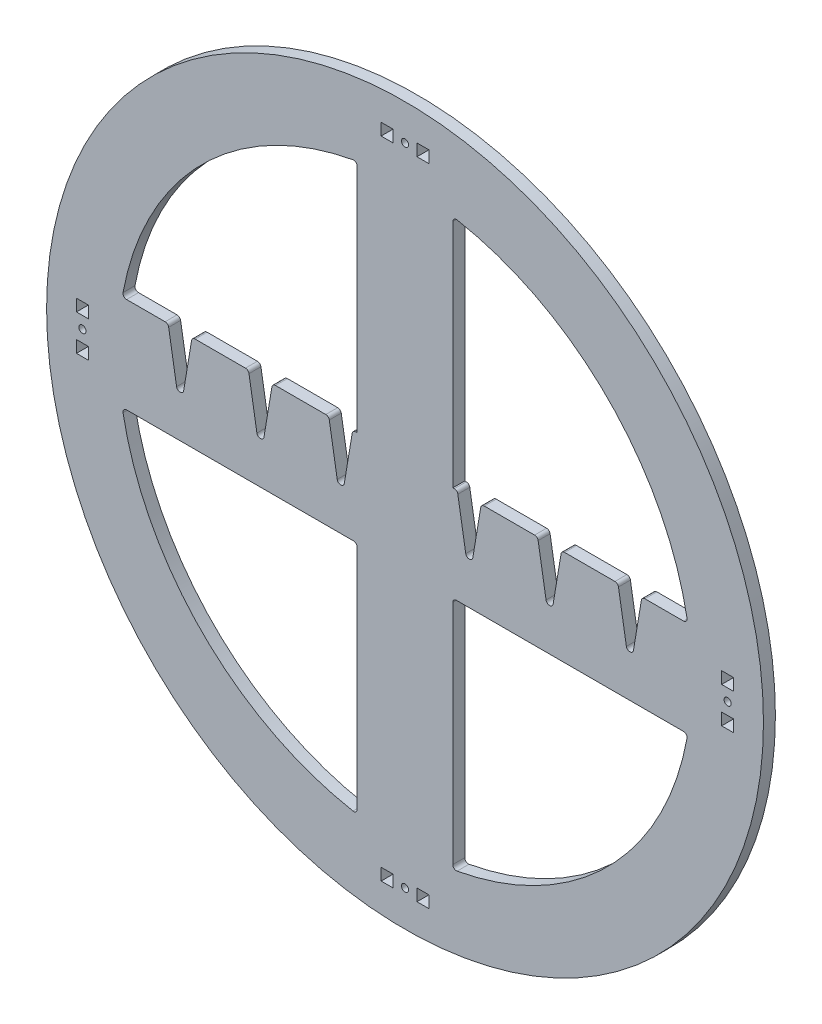
SolidWorks part; units mm, degrees
ref_plane "Front Plane" through (0, 0, 0) normal (0, 0, 1) x (1, 0, 0)
ref_plane "Top Plane" through (0, 0, 0) normal (0, 1, 0) x (1, 0, 0)
ref_plane "Right Plane" through (0, 0, 0) normal (1, 0, 0) x (0, 0, -1)
sketch "Esquisse1" plane through (0, 0, 0) normal (0, 0, 1) x (1, 0, 0)
  line L0 (0, 129.3346) -> (0, -149.5024) construction
  line L1 (-20, 118.3216) -> (-20, -118.3216) construction
  line L2 (20, 118.3216) -> (20, -118.3216) construction
  line L3 (-118.3216, 20) -> (118.3216, 20) construction
  line L4 (118.3216, -20) -> (-118.3216, -20) construction
  line L5 (-20, 118.3216) -> (-20, 20)
  line L7 (20, 118.3216) -> (20, 20)
  line L9 (118.3216, -20) -> (20, -20)
  line L10 (20, -20) -> (20, -118.3216)
  line L11 (-20, -118.3216) -> (-20, -20)
  line L12 (-20, -20) -> (-118.3216, -20)
  line L14 (-65.504, 20) -> (-60.504, -10)
  line L15 (-60.504, -10) -> (-55.504, 20)
  line L16 (-55.504, 20) -> (-31.8931, 20)
  line L17 (-31.8931, 20) -> (-26.8931, -10)
  line L18 (-26.8931, -10) -> (-21.8931, 20)
  line L19 (-20, 20) -> (-21.8931, 20)
  line L27 (-65.504, 20) -> (-89.1149, 20)
  line L28 (-89.1149, 20) -> (-94.1149, -10)
  line L29 (-94.1149, -10) -> (-99.1149, 20)
  line L30 (-99.1149, 20) -> (-118.3216, 20)
  line L31 (99.1149, 20) -> (118.3216, 20)
  line L32 (20, 20) -> (21.8931, 20)
  line L33 (26.8931, -10) -> (21.8931, 20)
  line L34 (94.1149, -10) -> (99.1149, 20)
  line L35 (89.1149, 20) -> (94.1149, -10)
  line L36 (65.504, 20) -> (89.1149, 20)
  line L37 (31.8931, 20) -> (26.8931, -10)
  line L38 (55.504, 20) -> (31.8931, 20)
  line L39 (60.504, -10) -> (55.504, 20)
  line L40 (65.504, 20) -> (60.504, -10)
  circle A0 centre (0, 0) radius 150
  circle A1 centre (0, 0) radius 120 construction
  circle A2 centre (0, 0) radius 135 construction
  arc A4 (-118.3216, 20) -> (-20, 118.3216) centre (0, 0) cw
  arc A5 (20, 118.3216) -> (118.3216, 20) centre (0, 0) cw
  arc A6 (118.3216, -20) -> (20, -118.3216) centre (0, 0) cw
  arc A7 (-20, -118.3216) -> (-118.3216, -20) centre (0, 0) cw
  point P8 (0, 0)
  point P26 (0, 0)
  line B0 (-135, -5) -> (-135, 5) construction
  line B1 (-137.5, -5) -> (-137.5, -10)
  line B2 (-137.5, -5) -> (-132.5, -5)
  line B3 (-132.5, -5) -> (-132.5, -10)
  line B4 (-137.5, -10) -> (-132.5, -10)
  line B5 (-137.5, 5) -> (-137.5, 10)
  line B6 (-137.5, 5) -> (-132.5, 5)
  line B7 (-132.5, 5) -> (-132.5, 10)
  line B8 (-137.5, 10) -> (-132.5, 10)
  line B9 (-135, 0) -> (-141.2802, 0) construction
  circle B10 centre (-135, 0) radius 1.5
  line B11 (-137.5, 10) -> (-132.5, 5) construction
  line B12 (-137.5, -5) -> (-132.5, -10) construction
  line B13 (-5, 135) -> (5, 135) construction
  line B14 (-5, 137.5) -> (-10, 137.5)
  line B15 (-5, 137.5) -> (-5, 132.5)
  line B16 (-5, 132.5) -> (-10, 132.5)
  line B17 (-10, 137.5) -> (-10, 132.5)
  line B18 (5, 137.5) -> (10, 137.5)
  line B19 (5, 137.5) -> (5, 132.5)
  line B20 (5, 132.5) -> (10, 132.5)
  line B21 (10, 137.5) -> (10, 132.5)
  line B22 (0, 135) -> (0, 141.2802) construction
  circle B23 centre (0, 135) radius 1.5
  line B24 (10, 137.5) -> (5, 132.5) construction
  line B25 (-5, 137.5) -> (-10, 132.5) construction
  line B26 (135, 5) -> (135, -5) construction
  line B27 (137.5, 5) -> (137.5, 10)
  line B28 (137.5, 5) -> (132.5, 5)
  line B29 (132.5, 5) -> (132.5, 10)
  line B30 (137.5, 10) -> (132.5, 10)
  line B31 (137.5, -5) -> (137.5, -10)
  line B32 (137.5, -5) -> (132.5, -5)
  line B33 (132.5, -5) -> (132.5, -10)
  line B34 (137.5, -10) -> (132.5, -10)
  line B35 (135, 0) -> (141.2802, 0) construction
  circle B36 centre (135, 0) radius 1.5
  line B37 (137.5, -10) -> (132.5, -5) construction
  line B38 (137.5, 5) -> (132.5, 10) construction
  line B39 (5, -135) -> (-5, -135) construction
  line B40 (5, -137.5) -> (10, -137.5)
  line B41 (5, -137.5) -> (5, -132.5)
  line B42 (5, -132.5) -> (10, -132.5)
  line B43 (10, -137.5) -> (10, -132.5)
  line B44 (-5, -137.5) -> (-10, -137.5)
  line B45 (-5, -137.5) -> (-5, -132.5)
  line B46 (-5, -132.5) -> (-10, -132.5)
  line B47 (-10, -137.5) -> (-10, -132.5)
  line B48 (0, -135) -> (0, -141.2802) construction
  circle B49 centre (0, -135) radius 1.5
  line B50 (-10, -137.5) -> (-5, -132.5) construction
  line B51 (5, -137.5) -> (10, -132.5) construction
sketch_block_instance "Trou M3 plots 5mm-53"
sketch_block "Trou M3 plots 5mm" parameters "D2"=3, "D1"=5, "D3"=5, "D4"=8
sketch_block_instance "Trou M3 plots 5mm-55"
sketch_block_instance "Trou M3 plots 5mm-56"
sketch_block_instance "Trou M3 plots 5mm-57" parameters "D1"=54.2135, "D3"=2.7166, "D4"=100.0009, "D5"=169.044, "D6"=84.522, "D2"=95.9432, "D8"=12.0196, "D9"=13.2129, "D10"=17.9289, "D11"=30, "D7"=4
extrude "Boss.-Extru.1" add sketch "Esquisse1" along normal blind 5
fillet "Congé1" radius 1.5 28 edges at (-118.3216, -20, 2.5) (-20, -20, 2.5) (118.3216, -20, 2.5) (20, -20, 2.5) (20, -118.3216, 2.5) (-20, -118.3216, 2.5) (20, 118.3216, 2.5) (-20, 118.3216, 2.5) (-55.504, 20, 2.5) (89.1149, 20, 2.5) (-21.8931, 20, 2.5) (-31.8931, 20, 2.5) (-26.8931, -10, 2.5) (-60.504, -10, 2.5) (118.3216, 20, 2.5) (94.1149, -10, 2.5) (60.504, -10, 2.5) (26.8931, -10, 2.5) (99.1149, 20, 2.5) (65.504, 20, 2.5) (55.504, 20, 2.5) (31.8931, 20, 2.5) (21.8931, 20, 2.5) (-118.3216, 20, 2.5) (-94.1149, -10, 2.5) (-99.1149, 20, 2.5) (-89.1149, 20, 2.5) (-65.504, 20, 2.5)
